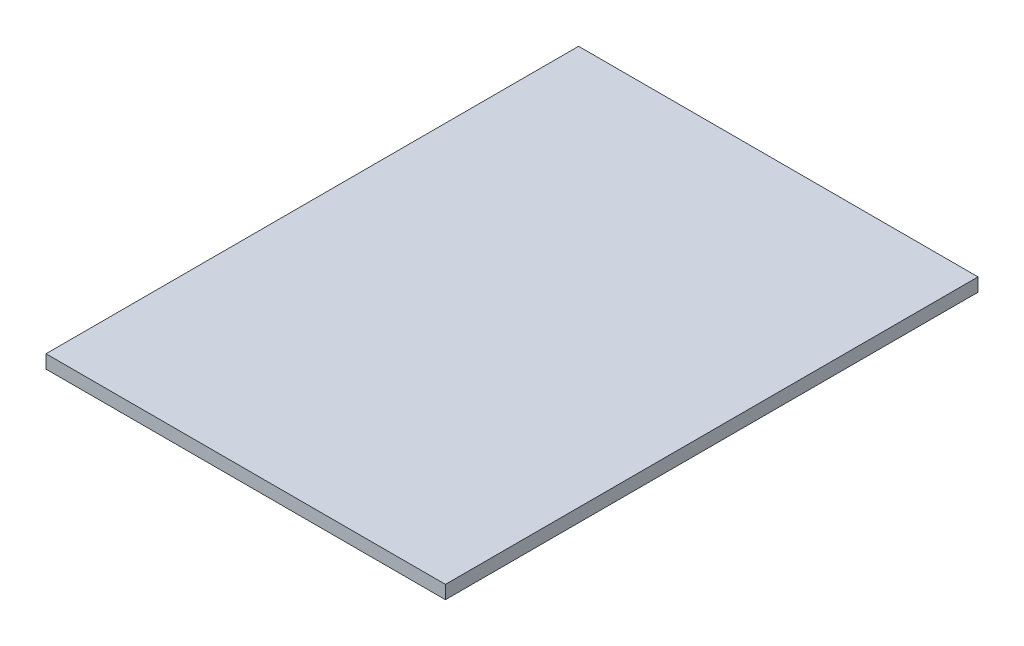
SolidWorks part; units mm, degrees
ref_plane "Front Plane" through (0, 0, 0) normal (0, 0, 1) x (1, 0, 0)
ref_plane "Top Plane" through (0, 0, 0) normal (0, 1, 0) x (1, 0, 0)
ref_plane "Right Plane" through (0, 0, 0) normal (1, 0, 0) x (0, 0, -1)
sketch "Sketch1" plane through (0, 0, 0) normal (0, 1, 0) x (1, 0, 0)
  line L1 (-47.625, -63.5) -> (47.625, -63.5)
  line L2 (-47.625, -63.5) -> (-47.625, 63.5)
  line L3 (-47.625, 63.5) -> (47.625, 63.5)
  line L4 (47.625, -63.5) -> (47.625, 63.5)
  line L5 (-47.625, -63.5) -> (47.625, 63.5) construction
  line L6 (-47.625, 63.5) -> (47.625, -63.5) construction
  point P0 (0, 0)
  dimension "D1" = 95.25
  dimension "D2" = 127
extrude "Boss-Extrude1" add sketch "Sketch1" along normal blind 3.175
